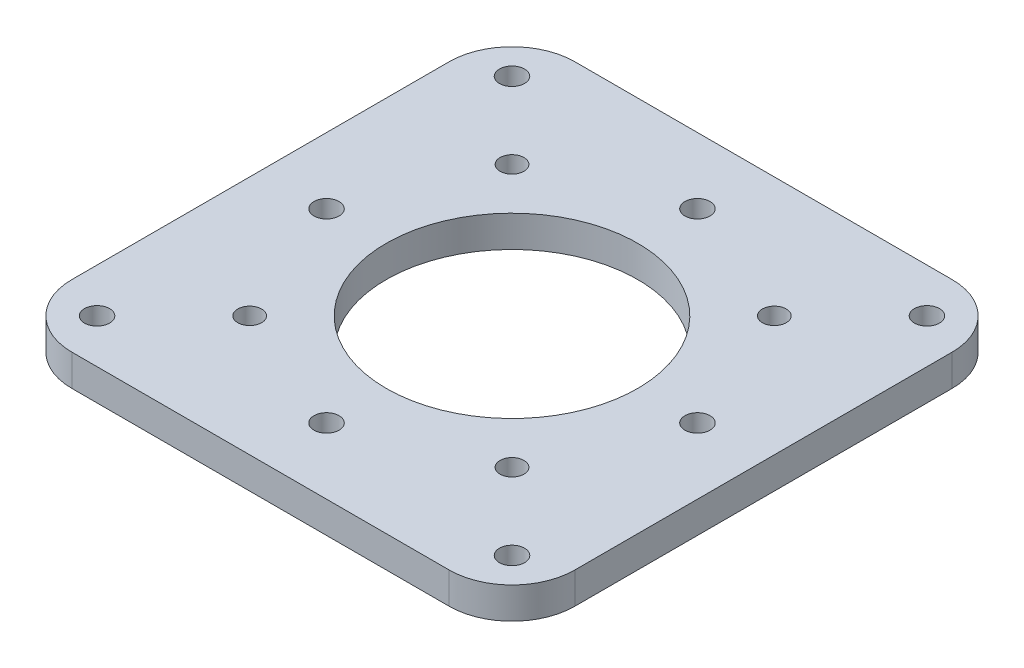
SolidWorks part; units mm, degrees
ref_plane "Спереди" through (0, 0, 0) normal (0, 0, 1) x (1, 0, 0)
ref_plane "Сверху" through (0, 0, 0) normal (0, 1, 0) x (1, 0, 0)
ref_plane "Справа" through (0, 0, 0) normal (1, 0, 0) x (0, 0, -1)
sketch "Эскиз1" plane through (0, 0, 0) normal (0, 1, 0) x (1, 0, 0)
  line L0 (0, 0) -> (36.9242, 36.9242) construction
  line L1 (-40, -40) -> (40, -40)
  line L2 (-40, -40) -> (-40, 40)
  line L3 (-40, 40) -> (40, 40)
  line L4 (40, -40) -> (40, 40)
  line L5 (0, 40) -> (0, -40) construction
  line L6 (-40, 0) -> (40, 0) construction
  line L8 (-33, -33) -> (33, -33) construction
  line L9 (-33, -33) -> (-33, 33) construction
  line L10 (-33, 33) -> (33, 33) construction
  line L11 (33, -33) -> (33, 33) construction
  line L12 (0, 33) -> (0, -33) construction
  line L13 (-33, 0) -> (33, 0) construction
  circle A0 centre (0, 0) radius 29.5 construction
  circle A1 centre (20.8597, 20.8597) radius 1.9
  circle A2 centre (20.8597, -20.8597) radius 1.9
  circle A3 centre (-20.8597, -20.8597) radius 1.9
  circle A4 centre (-20.8597, 20.8597) radius 1.9
  circle A5 centre (-33, 33) radius 2
  circle A6 centre (33, 33) radius 2
  circle A7 centre (33, -33) radius 2
  circle A8 centre (-33, -33) radius 2
  circle A9 centre (0, 0) radius 20
  circle A10 centre (0, 29.5) radius 2
  circle A11 centre (29.5, 0) radius 2
  circle A12 centre (0, -29.5) radius 2
  circle A13 centre (-29.5, 0) radius 2
  point P0 (0, 0)
  point P18 (0, 0)
  point P35 (0, 0)
  dimension "D3" = 45
  dimension "D4" = 3.8
  dimension "D5" = 59
  dimension "D8" = 4
  dimension "D9" = 93.3381
  dimension "D6" = 40
  dimension "D10" = 4
  dimension "D1" = 46.669
  dimension "D2" = 80
  dimension "D7" = 66
extrude "Бобышка-Вытянуть1" add sketch "Эскиз1" along normal blind 5
fillet "Скругление5" radius 10 4 edges at (-40, 2.5, -40) (40, 2.5, -40) (-40, 2.5, 40) (40, 2.5, 40)
